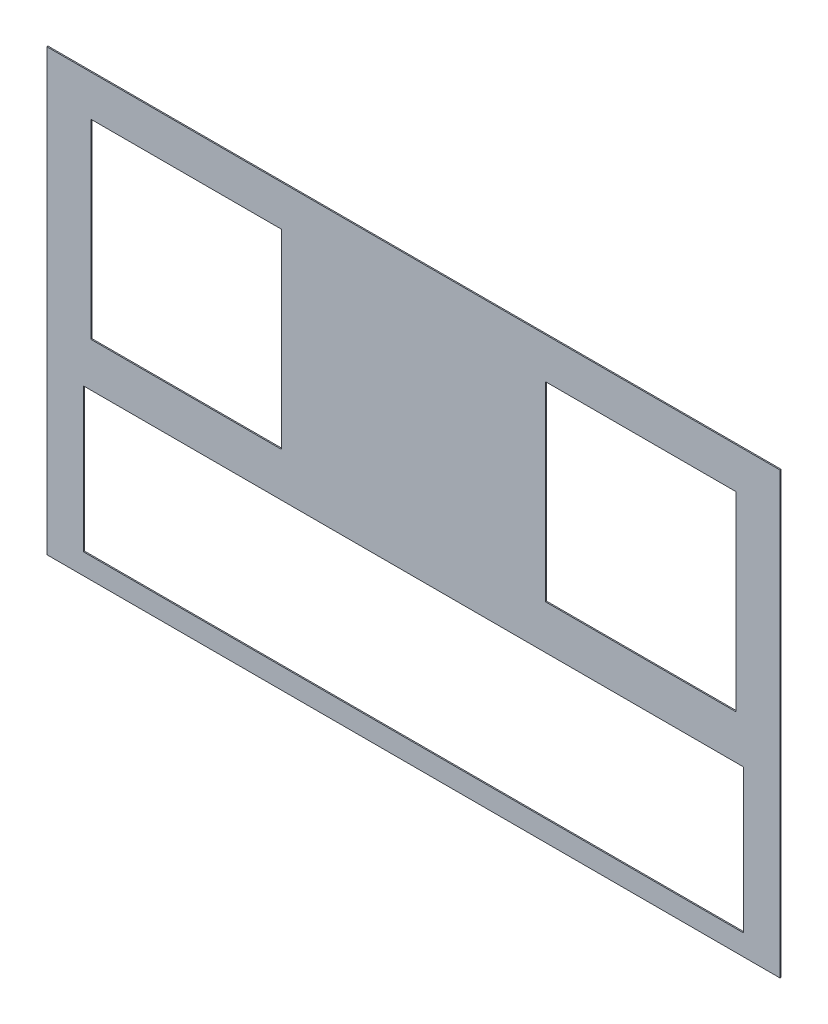
SolidWorks part; units mm, degrees
material "ABS"
ref_plane "Front Plane" through (0, 0, 0) normal (0, 0, 1) x (1, 0, 0)
ref_plane "Top Plane" through (0, 0, 0) normal (0, 1, 0) x (1, 0, 0)
ref_plane "Right Plane" through (0, 0, 0) normal (1, 0, 0) x (0, 0, -1)
sketch "Sketch1" plane through (0, 0, 0) normal (0, 0, 1) x (1, 0, 0)
  line L0 (-1250, 0) -> (0, 0) construction
  line L1 (-1250, 750) -> (0, 750)
  line L2 (-1250, 750) -> (-1250, -750)
  line L3 (-1250, -750) -> (1250, -750)
  line L4 (1250, 750) -> (1250, -750)
  line L5 (0, 0) -> (1250, 0) construction
  line L6 (0, 750) -> (1250, 750)
  line L7 (0, 750) -> (0, 0) construction
  line L8 (0, 0) -> (0, -750) construction
  dimension "D1" = 2500
  dimension "D2" = 1500
extrude "Boss-Extrude1" add sketch "Sketch1" along normal blind 4
sketch "Sketch3" plane through (0, 0, 4) normal (0, 0, 1) x (1, 0, 0)
  line L0 (-450, 286) -> (450, 286) construction
  line L1 (-1100, 611) -> (-450, 611)
  line L2 (-1100, 611) -> (-1100, -39)
  line L3 (-1100, -39) -> (-450, -39)
  line L4 (-450, 611) -> (-450, -39)
  line L5 (450, 611) -> (1100, 611)
  line L6 (450, 611) -> (450, -39)
  line L7 (450, -39) -> (1100, -39)
  line L8 (1100, 611) -> (1100, -39)
  line L13 (0, 0) -> (0, 286) construction
  line L16 (-450, -39) -> (450, -39) construction
  line L17 (-1125, -189) -> (1125, -189)
  line L18 (-1125, -189) -> (-1125, -679)
  line L19 (-1125, -679) -> (1125, -679)
  line L20 (1125, -189) -> (1125, -679)
  line L21 (0, -39) -> (0, -100) construction
  line L22 (0, -250) -> (0, -189) construction
  line L23 (-1250, -750) -> (1250, -750) construction
  dimension "D1" = 650
  dimension "D2" = 650
  dimension "D3" = 150
  dimension "D5" = 71
  dimension "D7" = 900
  dimension "D8" = 490
  dimension "D9" = 2250
extrude "Cut-Extrude1" cut sketch "Sketch3" against normal through all
sketch "Sketch2" [suppressed] plane through (0, 0, 20) normal (0, 0, 1) x (1, 0, 0)
  line L0 (-940, 600) -> (-300, 600) construction
  line L1 (-620, 600) -> (-620, 560) construction
  line L2 (300, 600) -> (940, 600) construction
  line L3 (-300, 560) -> (-940, 560) construction
  line L5 (620, 560) -> (620, 600) construction
  line L8 (-960, -140) -> (-560, -140) construction
  line L10 (940, 560) -> (300, 560) construction
  line L11 (-560, -140) -> (-560, -40) construction
  line L12 (-560, -40) -> (-960, -40) construction
  line L13 (-960, -40) -> (-960, -140) construction
  line L14 (-560, -90) -> (-480, -90) construction
  line L15 (-480, 70) -> (-480, -250) construction
  text T0 "WYNNUM" font "Arial" height 100
  text T1 "<b>VISITORS</b>" font "Arial" height 100
  text T2 "TIME" font "Arial" height 100
  dimension "D1" = 640
  dimension "D2" = 100
  dimension "D3" = 80
  dimension "D4" = 400
  dimension "D5" = 40
extrude "Boss-Extrude2" [suppressed] add sketch "Sketch2" along normal blind 3
ref_plane "Plane1" through (0, -434, 0) normal (0, -1, 0) x (-1, 0, 0)
ref_plane "Plane2" [suppressed] through (0, -90, 0) normal (0, 1, 0) x (1, 0, 0)
ref_plane "Plane3" through (0, 286, 0) normal (0, -1, 0) x (-1, 0, 0)
ref_plane "Plane4" through (-775, 0, 0) normal (1, 0, 0) x (0, 0, -1)
ref_plane "Plane5" through (775, 0, 0) normal (-1, 0, 0) x (0, 0, 1)
